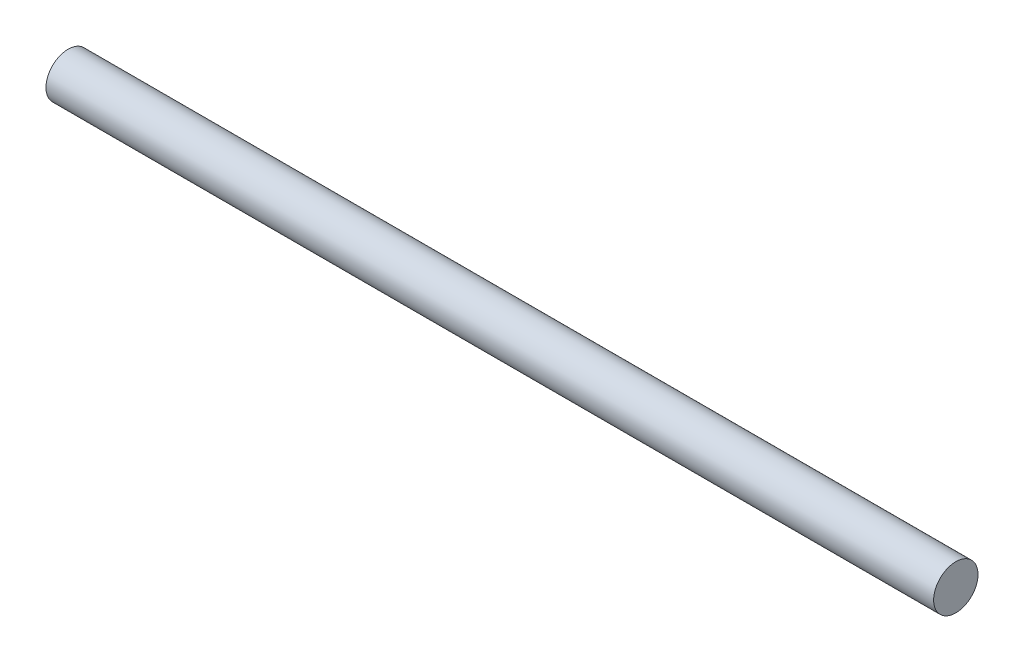
SolidWorks part; units mm, degrees
ref_plane "Front Plane" through (0, 0, 0) normal (0, 0, 1) x (1, 0, 0)
ref_plane "Top Plane" through (0, 0, 0) normal (0, 1, 0) x (1, 0, 0)
ref_plane "Right Plane" through (0, 0, 0) normal (1, 0, 0) x (0, 0, -1)
sketch "Esquisse1" plane through (0, 0, 0) normal (1, 0, 0) x (0, 0, -1)
  circle A0 centre (0, 0) radius 2.5
  dimension "D1" = 5
extrude "Boss.-Extru.1" add sketch "Esquisse1" along normal blind 100
